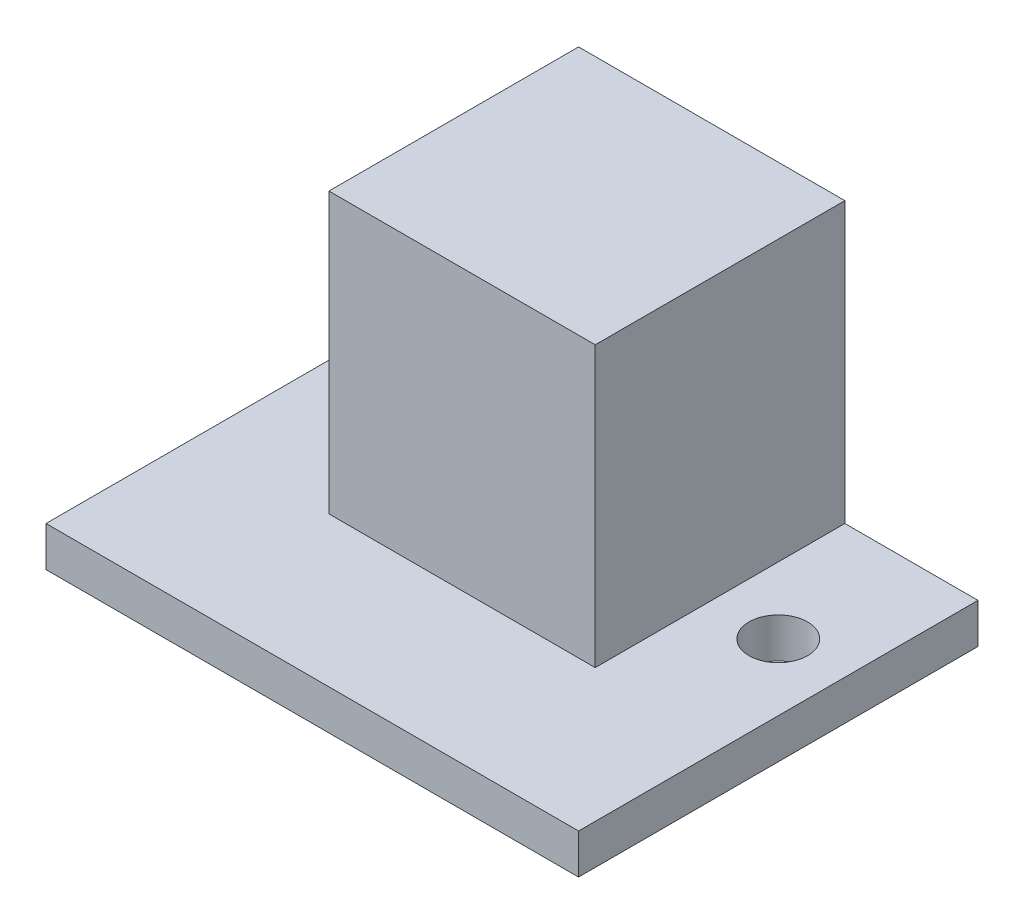
SolidWorks part; units mm, degrees
ref_plane "Plan de face" through (0, 0, 0) normal (0, 0, 1) x (1, 0, 0)
ref_plane "Plan de dessus" through (0, 0, 0) normal (0, 1, 0) x (1, 0, 0)
ref_plane "Plan de droite" through (0, 0, 0) normal (1, 0, 0) x (0, 0, -1)
sketch "Esquisse3" plane through (0, 0, 0) normal (0, 1, 0) x (1, 0, 0)
  line L0 (-0.0516, 15.6297) -> (-0.0516, -14.3703)
  line L1 (-20.0516, 15.6297) -> (19.9484, 15.6297)
  line L2 (-20.0516, 15.6297) -> (-20.0516, -14.3703)
  line L3 (-20.0516, -14.3703) -> (19.9484, -14.3703)
  line L4 (19.9484, 15.6297) -> (19.9484, -14.3703)
  line L5 (-20.0516, 0.6297) -> (19.9484, 0.6297)
  line L6 (19.9484, 15.6297) -> (19.9484, 5.6297)
  line L7 (19.9484, 5.6297) -> (-20.0516, 5.6297)
  line L8 (-0.0516, 5.6297) -> (-15.0516, 5.6297)
  line L9 (-15.0516, 5.6297) -> (14.9484, 5.6297)
  line L10 (-0.0516, 5.6297) -> (-10.0516, 5.6297)
  line L11 (-10.0516, 5.6297) -> (9.9484, 5.6297)
  line L12 (9.9484, 5.6297) -> (9.9484, -14.3703)
  line L13 (9.9484, -14.3703) -> (-10.0516, -14.3703)
  line L14 (-10.0516, -14.3703) -> (-10.0516, 5.6297)
  line L15 (-10.0516, 15.6297) -> (-10.0516, 5.6297)
  line L16 (9.9484, 5.6297) -> (9.9484, 15.6297)
  circle A0 centre (14.9484, 5.6297) radius 2.2
  circle A1 centre (-15.0516, 5.6297) radius 2.2
extrude "Boss.-Extru.1" add sketch "Esquisse3" along normal blind 3 contours L3 L14 L5 L2 | L5 L12 L3 L4 | A1 L9 L15 L1 L2 L7 | A1 L7 L2 L5 L14 L9 | L1 L15 L7 L0 | L9 L16 L1 L0 | A0 L7 L4 L1 L16 L9 | A0 L9 L12 L5 L4 L7 | L12 L5 L0 L3 | L14 L3 L0 L5 | L12 L9 L0 L5 | L14 L5 L0 L7
sketch "Esquisse4" plane through (0, 3, 0) normal (0, 1, 0) x (1, 0, 0)
  line L0 (-20.0516, 0.6297) -> (19.9484, 0.6297)
  line L1 (-20.0516, 15.6297) -> (-20.0516, -14.3703) construction
  line L2 (19.9484, 15.6297) -> (19.9484, -14.3703) construction
  line L3 (19.9484, 0.6297) -> (-0.0516, 15.6297)
  line L4 (-20.0516, 15.6297) -> (19.9484, 15.6297) construction
  line L5 (-0.0516, 15.6297) -> (-0.0516, -14.3703)
  line L6 (-20.0516, -14.3703) -> (19.9484, -14.3703) construction
  line L7 (-0.0516, -14.3703) -> (-20.0516, 0.6297)
  line L8 (-0.0516, 15.6297) -> (-20.0516, 0.6297)
  line L9 (-0.0516, -14.3703) -> (19.9484, 0.6297)
  line L10 (-15.0516, 5.6297) -> (14.9484, 5.6297)
  line L11 (14.9484, 5.6297) -> (14.9484, 15.6297)
  line L12 (-15.0516, 5.6297) -> (-15.0516, 15.6297)
  line L13 (-15.0516, 15.6297) -> (14.9484, 15.6297)
  line L14 (-0.0516, 5.6297) -> (-10.0516, 5.6297)
  line L15 (-0.0516, 5.6297) -> (9.9484, 5.6297)
  line L16 (-10.0516, 5.6297) -> (-10.0516, 15.6297)
  line L17 (-10.0516, 15.6297) -> (9.9484, 15.6297)
  line L18 (-15.0516, 5.6297) -> (-15.0516, -3.1203)
  line L19 (-15.0516, -3.1203) -> (14.9484, -3.1203)
  line L20 (14.9484, -3.1203) -> (14.9484, 5.6297)
  line L21 (-10.0516, 5.6297) -> (-10.0516, -3.1203)
  line L22 (9.9484, 5.6297) -> (9.9484, -3.1203)
  line L23 (9.9484, -3.1203) -> (9.9484, 15.6297)
  line M5 (19.9484, 15.6297) -> (-20.0516, 15.6297)
extrude "Boss.-Extru.2" add sketch "Esquisse4" along normal blind 17 contours L10 L21 L0 L5 | L0 L21 L19 L5 | L22 L0 L5 L19 | L22 L10 L5 L0 | L10 L23 L3 L5 | L16 L10 L5 L8 | L16 L8 M5 | L3 L23 L13
sketch "Esquisse5" plane through (0, 20, 0) normal (0, 1, 0) x (1, 0, 0)
  line L0 (9.9484, -3.1203) -> (-10.0516, -3.1203)
  line L1 (-10.0516, -3.1203) -> (-10.0516, 15.6297)
  line L2 (-10.0516, 15.6297) -> (9.9484, 15.6297)
  line L3 (9.9484, 15.6297) -> (9.9484, -3.1203)
extrude "Boss.-Extru.4" add sketch "Esquisse5" along normal blind 4
